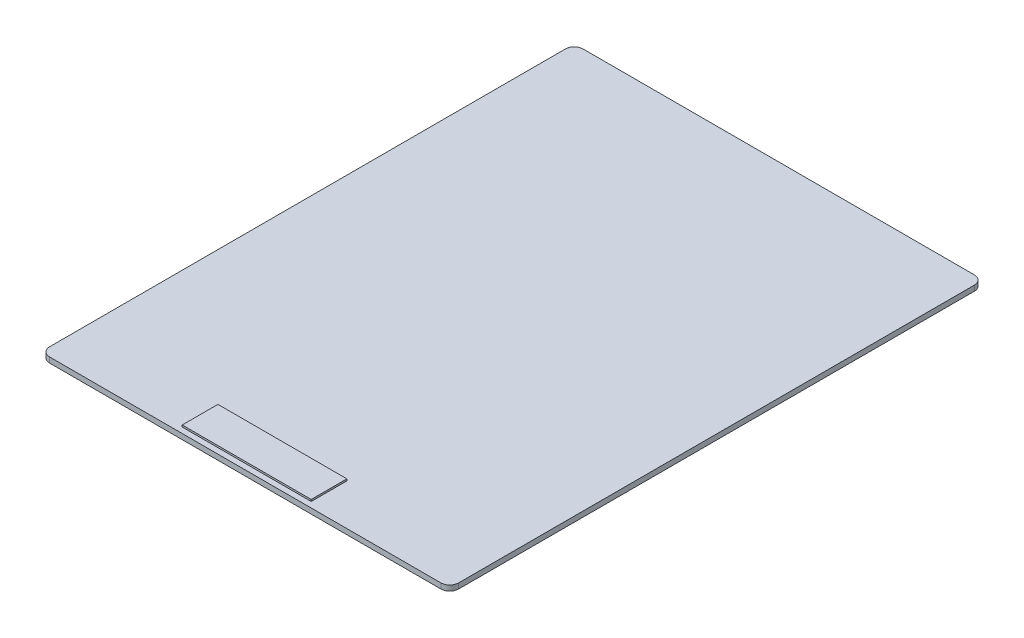
SolidWorks part; units mm, degrees
ref_plane "Front Plane" through (0, 0, 0) normal (0, 0, 1) x (1, 0, 0)
ref_plane "Top Plane" through (0, 0, 0) normal (0, 1, 0) x (1, 0, 0)
ref_plane "Right Plane" through (0, 0, 0) normal (1, 0, 0) x (0, 0, -1)
sketch "Sketch1" plane through (0, 0, 0) normal (0, 1, 0) x (1, 0, 0)
  line L1 (554.2978, 674.4014) -> (324.2978, 674.4014)
  line L2 (554.2978, 674.4014) -> (554.2978, 974.4014)
  line L3 (554.2978, 974.4014) -> (324.2978, 974.4014)
  line L4 (324.2978, 674.4014) -> (324.2978, 974.4014)
  dimension "D1" = 230
  dimension "D2" = 300
extrude "Boss-Extrude1" add sketch "Sketch1" along normal blind 3
fillet "Fillet1" radius 5 4 edges at (554.2978, 1.5, -674.4014) (324.2978, 1.5, -674.4014) (324.2978, 1.5, -974.4014) (554.2978, 1.5, -974.4014)
sketch "Sketch2" plane through (0, 3, 0) normal (0, 1, 0) x (1, 0, 0)
  line L1 (473.2146, 677.5586) -> (400.6845, 677.5586)
  line L2 (473.2146, 677.5586) -> (473.2146, 697.6322)
  line L3 (473.2146, 697.6322) -> (400.6845, 697.6322)
  line L4 (400.6845, 677.5586) -> (400.6845, 697.6322)
extrude "Boss-Extrude2" add sketch "Sketch2" along normal blind 1
